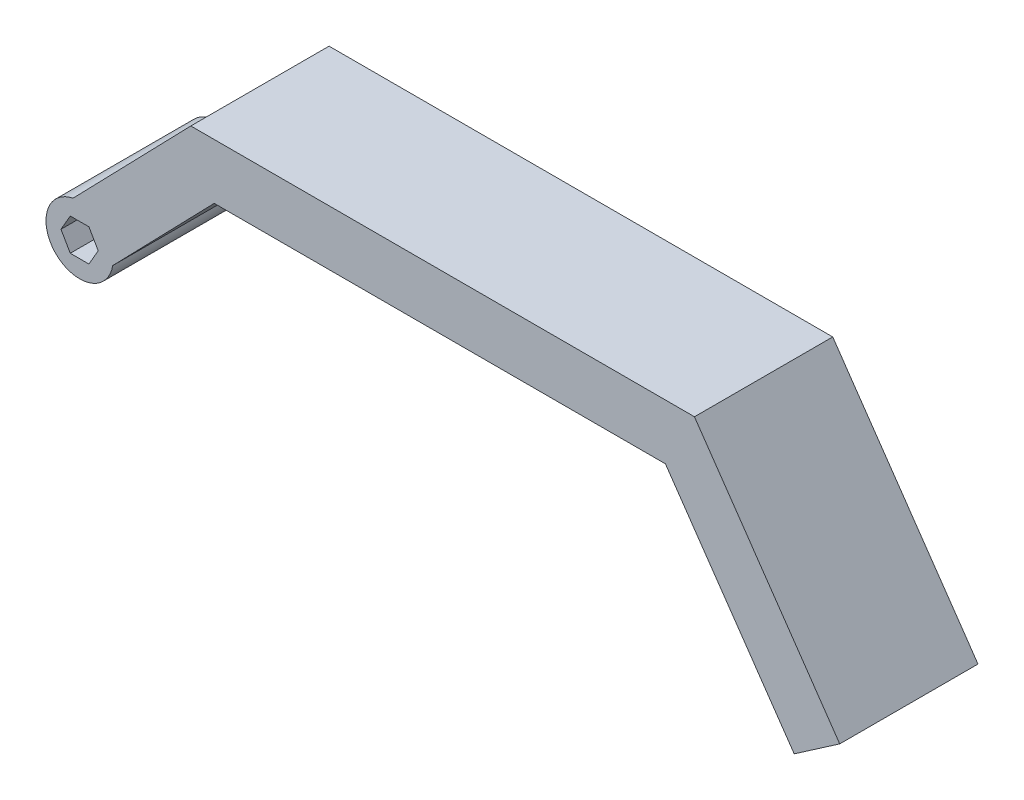
SolidWorks part; units mm, degrees
ref_plane "Front Plane" through (0, 0, 0) normal (0, 0, 1) x (1, 0, 0)
ref_plane "Top Plane" through (0, 0, 0) normal (0, 1, 0) x (1, 0, 0)
ref_plane "Right Plane" through (0, 0, 0) normal (1, 0, 0) x (0, 0, -1)
sketch "Sketch1" plane through (0, 0, 0) normal (0, 0, 1) x (1, 0, 0)
  line L0 (0, 0) -> (26.6691, 27.4989) construction
  line L1 (4.0415, 0) -> (2.0207, 3.5)
  line L2 (2.0207, 3.5) -> (-2.0207, 3.5)
  line L3 (-2.0207, 3.5) -> (-4.0415, 0)
  line L4 (-4.0415, 0) -> (-2.0207, -3.5)
  line L5 (-2.0207, -3.5) -> (2.0207, -3.5)
  line L6 (2.0207, -3.5) -> (4.0415, 0)
  line L7 (26.6691, 27.4989) -> (130.2673, 27.4989) construction
  line L8 (130.2673, 27.4989) -> (160, -15.6219) construction
  line L9 (7.1884, -1.2063) -> (29.2084, 21.4989)
  line L10 (29.2084, 21.4989) -> (127.1164, 21.4989)
  line L11 (127.1164, 21.4989) -> (155.0604, -19.0278)
  line L12 (-1.4259, 7.1481) -> (24.1298, 33.4989)
  line L13 (24.1298, 33.4989) -> (133.4182, 33.4989)
  line L14 (133.4182, 33.4989) -> (164.9396, -12.2159)
  line L15 (155.0604, -19.0278) -> (164.9396, -12.2159)
  line L16 (-4.3071, 4.1772) -> (24.1298, 33.4989) construction
  line L17 (4.3071, -4.1772) -> (29.2084, 21.4989) construction
  arc A0 (-1.4259, 7.1481) -> (7.1884, -1.2063) centre (0, 0) ccw
  circle A1 centre (0, 0) radius 3.5 construction
  dimension "D1" = 7
  dimension "D2" = 6
  dimension "D4" = 160
  dimension "D3" = 6
extrude "Boss-Extrude1" add sketch "Sketch1" along normal blind 30
